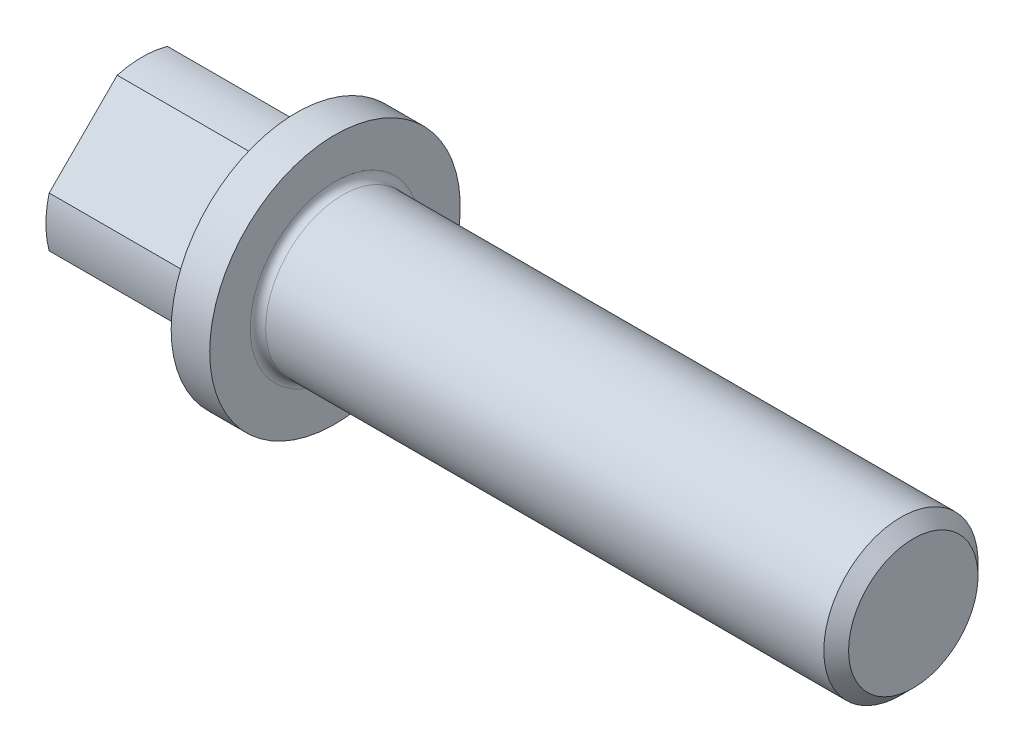
SolidWorks part; units mm, degrees
revolve "Base-Revolve" add sketch "BodySke"
sketch "BodySke" plane through (0, 0, 0) normal (0, 0, 1) x (1, 0, 0)
  line L0 (0, 0) -> (0, 9.75)
  line L1 (0, 9.75) -> (15, 9.75)
  line L2 (15, 9.75) -> (15, 6)
  line L3 (15, 6) -> (59.036, 6)
  line L4 (60, 5.036) -> (60, 0)
  line L5 (60, 0) -> (0, 0)
  line L6 (-31.75, 0) -> (127, 0) construction
  line L8 (60, 5.036) -> (59.036, 6)
  line L10 (60, -5.036) -> (59.036, -6) construction
  line L11 (16.75, 4.525) -> (16.75, -1.825) construction
  line L12 (15, 4.525) -> (15, -1.825) construction
  line L13 (0, 4.525) -> (0, -1.825) construction
  dimension "Length" = 45
  dimension "Body_ch_ang" = 45
  dimension "Diameter" = 12
  dimension "Minor_dia" = 10.072
  dimension "Advance" = 1.75
  dimension "Thread_nom" = 45
  dimension "Thread_length" = 60
  dimension "Head_dia" = 19.5
  dimension "Head_ht" = 15
cosmetic thread "ThreadCosmetic" [suppressed]
fillet "Fillet1" radius 0.6 1 edges at (15, 0, 6)
fillet "Fillet2" radius 0.6 1 edges at (0, 0, 9.75)
ref_plane "Plane1" through (0, 0, 0) normal (0, 0, 1) x (1, 0, 0)
ref_plane "Plane2" through (0, 0, 0) normal (0, 1, 0) x (1, 0, 0)
ref_plane "Plane3" through (0, 0, 0) normal (1, 0, 0) x (0, 0, -1)
sketch "ThdSchSke" plane through (0, 0, 0) normal (0, 0, 1) x (1, 0, 0)
  line L0 (17.625, -5.036) -> (16.95, -6)
  line L1 (17.625, -5.036) -> (18.3, -6)
  line L2 (18.3, -6) -> (18.3, -7.5)
  line L3 (-3.175, 0) -> (5.1513, 0) construction
  line L4 (0, 9.15) -> (0, -9.15) construction
  line L5 (18.3, -7.5) -> (16.95, -7.5)
  line L6 (16.95, -7.5) -> (16.95, -6)
  dimension "Thread_minor" = 10.072
  dimension "Diameter" = 12
  dimension "Start" = 17.625
revolve "ThreadSchematic" [suppressed] cut sketch "ThdSchSke" angle 360 about L3
pattern_linear "ThdSchPat" [suppressed]
sketch "SqrDrvSke" plane through (0, 0, 0) normal (1, 0, 0) x (0, 0, -1)
  line L0 (1.9504, -7.2419) -> (7.2419, -1.9504)
  line L1 (-1.9504, -7.2419) -> (-7.2419, -1.9504)
  line L2 (7.2419, 1.9504) -> (1.9504, 7.2419)
  line L3 (-7.2419, 1.9504) -> (-1.9504, 7.2419)
  line L4 (0, 9.525) -> (0, -9.525) construction
  line L5 (6.35, 0) -> (-7.0711, 0) construction
  arc A0 (1.9504, 7.2419) -> (-1.9504, 7.2419) centre (0, 0) ccw
  arc A1 (7.2419, -1.9504) -> (7.2419, 1.9504) centre (0, 0) ccw
  arc A2 (-1.9504, -7.2419) -> (1.9504, -7.2419) centre (0, 0) ccw
  arc A3 (-7.2419, 1.9504) -> (-7.2419, -1.9504) centre (0, 0) ccw
extrude "Square drive" cut sketch "SqrDrvSke" along normal blind 12 flip side to cut
equation "\"Thread_minor@ThreadCosmetic\"  =  \"Minor_dia@BodySke\""
equation "\"Thread_length@ThreadCosmetic\" = ((sgn( (\"Length@BodySke\" - \"Advance@BodySke\" * 1.5) - \"Thread_nom@BodySke\" )-1)*( (\"Length@BodySke\" - \"Advance@BodySke\" * 1.5) - \"Thread_nom@BodySke\" ))/-2+ \"Thread_nom@BodySke\""
equation "\"Thread_minor@ThdSchSke\" = \"Minor_dia@BodySke\""
equation "\"Diameter@ThdSchSke\" = \"Diameter@BodySke\""
equation "\"Overcut@ThdSchSke\" = \"Diameter@BodySke\" * 1.25"
equation "\"Start@ThdSchSke\" = \"Head_ht@BodySke\" + \"Length@BodySke\" - \"Thread_length@ThreadCosmetic\"  '---Non-countersunk---"
equation "\"Num_threads@ThdSchPat\" = int( \"Thread_length@ThreadCosmetic\" / \"Advance@BodySke\" + 0.999 )  + 1"
equation "\"Advance@ThdSchPat\" = \"Thread_length@ThreadCosmetic\" /  (\"Num_threads@ThdSchPat\" - 1) 'relax it"
equation "\"Num_threads@ThdSchPat\" = \"Num_threads@ThdSchPat\" - sgn( \"Num_threads@ThdSchPat\" - 1) '---chamfered tips only---"
equation "\"DriveDia@SqrDrvSke\" = \"Head_ht@BodySke\""
